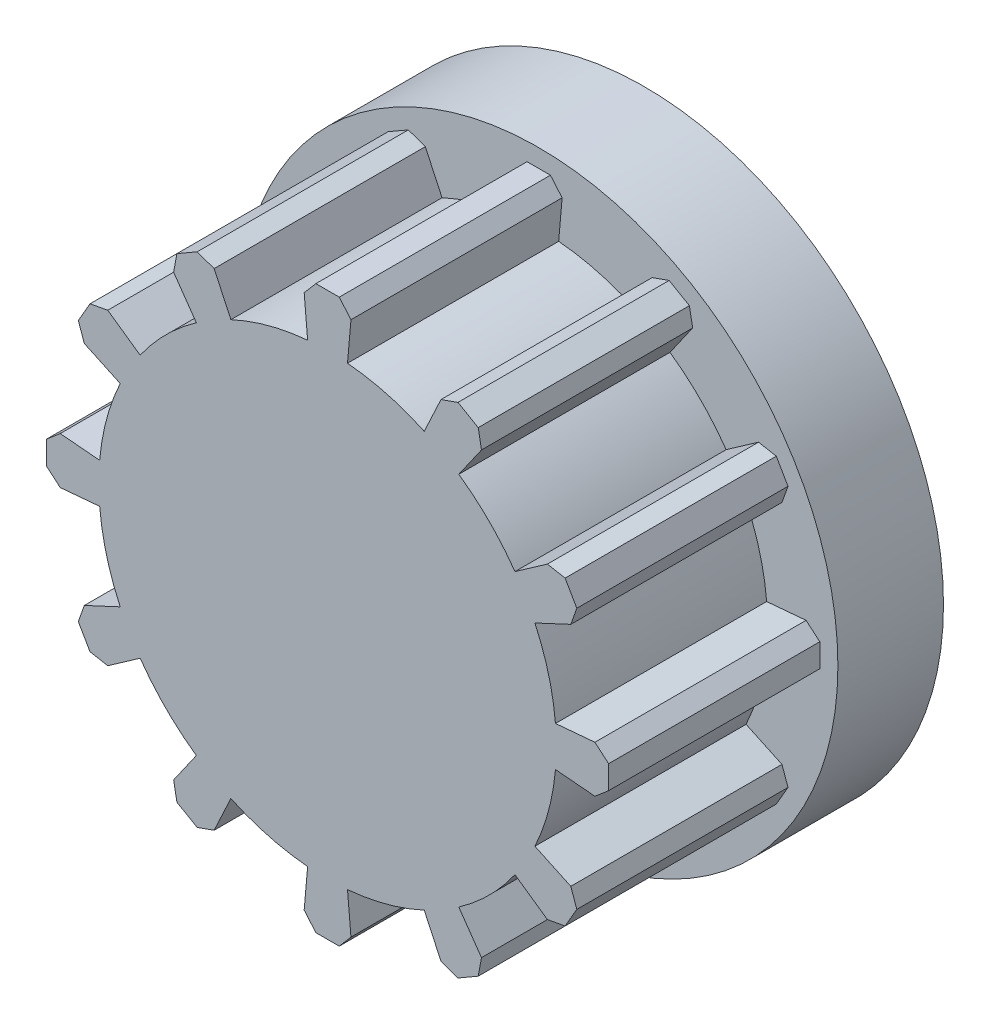
SolidWorks part; units mm, degrees
ref_plane "Front Plane" through (0, 0, 0) normal (0, 0, 1) x (1, 0, 0)
ref_plane "Top Plane" through (0, 0, 0) normal (0, 1, 0) x (1, 0, 0)
ref_plane "Right Plane" through (0, 0, 0) normal (1, 0, 0) x (0, 0, -1)
sketch "Sketch1" plane through (0, 0, 0) normal (0, 0, 1) x (1, 0, 0)
  circle A0 centre (0, 0) radius 8.5
extrude "Boss-Extrude1" add sketch "Sketch1" along normal blind 3
sketch "Sketch2" plane through (0, 0, 3) normal (0, 0, 1) x (1, 0, 0)
  line L0 (2.747, 5.891) -> (3.2225, 6.9106)
  line L1 (-0.5665, 6.4753) -> (-0.6646, 7.596) construction
  line L2 (-0.5665, 6.4753) -> (-0.6646, 7.596)
  line L3 (3.2225, 6.9106) -> (3.705, 7.0818)
  line L4 (-0.6646, 7.596) -> (-0.3323, 7.9855)
  line L5 (0.5665, 6.4753) -> (0.6646, 7.596)
  line L6 (0.6646, 7.596) -> (0.3323, 7.9855)
  line L7 (-0.3323, 7.9855) -> (0.3323, 7.9855)
  line L9 (3.7282, 5.3245) -> (4.3735, 6.246)
  line L10 (4.3735, 6.246) -> (4.2805, 6.7495)
  line L11 (3.705, 7.0818) -> (4.2805, 6.7495)
  line L13 (5.3245, 3.7282) -> (6.246, 4.3735)
  line L14 (6.246, 4.3735) -> (6.7495, 4.2805)
  line L15 (5.891, 2.747) -> (6.9106, 3.2225)
  line L16 (6.9106, 3.2225) -> (7.0818, 3.705)
  line L17 (6.7495, 4.2805) -> (7.0818, 3.705)
  line L19 (6.4753, 0.5665) -> (7.596, 0.6646)
  line L20 (7.596, 0.6646) -> (7.9855, 0.3323)
  line L21 (6.4753, -0.5665) -> (7.596, -0.6646)
  line L22 (7.596, -0.6646) -> (7.9855, -0.3323)
  line L23 (7.9855, 0.3323) -> (7.9855, -0.3323)
  line L25 (5.891, -2.747) -> (6.9106, -3.2225)
  line L26 (6.9106, -3.2225) -> (7.0818, -3.705)
  line L27 (5.3245, -3.7282) -> (6.246, -4.3735)
  line L28 (6.246, -4.3735) -> (6.7495, -4.2805)
  line L29 (7.0818, -3.705) -> (6.7495, -4.2805)
  line L30 (7.253, -4.1875) -> (7.7711, -4.4867) construction
  line L31 (3.7282, -5.3245) -> (4.3735, -6.246)
  line L32 (4.3735, -6.246) -> (4.2805, -6.7495)
  line L33 (2.747, -5.891) -> (3.2225, -6.9106)
  line L34 (3.2225, -6.9106) -> (3.705, -7.0818)
  line L35 (4.2805, -6.7495) -> (3.705, -7.0818)
  line L37 (0.5665, -6.4753) -> (0.6646, -7.596)
  line L38 (0.6646, -7.596) -> (0.3323, -7.9855)
  line L39 (-0.5665, -6.4753) -> (-0.6646, -7.596)
  line L40 (-0.6646, -7.596) -> (-0.3323, -7.9855)
  line L41 (0.3323, -7.9855) -> (-0.3323, -7.9855)
  line L43 (-2.747, -5.891) -> (-3.2225, -6.9106)
  line L44 (-3.2225, -6.9106) -> (-3.705, -7.0818)
  line L45 (-3.7282, -5.3245) -> (-4.3735, -6.246)
  line L46 (-4.3735, -6.246) -> (-4.2805, -6.7495)
  line L47 (-3.705, -7.0818) -> (-4.2805, -6.7495)
  line L49 (-5.3245, -3.7282) -> (-6.246, -4.3735)
  line L50 (-6.246, -4.3735) -> (-6.7495, -4.2805)
  line L51 (-5.891, -2.747) -> (-6.9106, -3.2225)
  line L52 (-6.9106, -3.2225) -> (-7.0818, -3.705)
  line L53 (-6.7495, -4.2805) -> (-7.0818, -3.705)
  line L55 (-6.4753, -0.5665) -> (-7.596, -0.6646)
  line L56 (-7.596, -0.6646) -> (-7.9855, -0.3323)
  line L57 (-6.4753, 0.5665) -> (-7.596, 0.6646)
  line L58 (-7.596, 0.6646) -> (-7.9855, 0.3323)
  line L59 (-7.9855, -0.3323) -> (-7.9855, 0.3323)
  line L61 (-5.891, 2.747) -> (-6.9106, 3.2225)
  line L62 (-6.9106, 3.2225) -> (-7.0818, 3.705)
  line L63 (-5.3245, 3.7282) -> (-6.246, 4.3735)
  line L64 (-6.246, 4.3735) -> (-6.7495, 4.2805)
  line L65 (-7.0818, 3.705) -> (-6.7495, 4.2805)
  line L67 (-3.7282, 5.3245) -> (-4.3735, 6.246)
  line L68 (-4.3735, 6.246) -> (-4.2805, 6.7495)
  line L69 (-2.747, 5.891) -> (-3.2225, 6.9106)
  line L70 (-3.2225, 6.9106) -> (-3.705, 7.0818)
  line L71 (-4.2805, 6.7495) -> (-3.705, 7.0818)
  circle A1 centre (0, 0) radius 6.5
  point P102 (0, 0)
  dimension "D1" = 12
  dimension "D2" = 13
  dimension "D4" = 7.625
sketch "Sketch4" plane through (0, 0, 0) normal (0, 0, -1) x (-1, 0, 0)
  line L0 (-3.25, 0.9682) -> (3.25, 0.9682)
  line L1 (-3.25, -0.9682) -> (3.25, -0.9682)
  line L2 (-5, 0) -> (5, 0) construction
  arc A0 (-3.25, 0.9682) -> (-3.25, -0.9682) centre (-5, 0) ccw
  arc A1 (3.25, -0.9682) -> (3.25, 0.9682) centre (5, 0) ccw
  point P2 (0.1492, 0.8866)
  point P3 (0.1492, 0.8866)
  point P8 (0, 0)
  dimension "D1" = 10
extrude "Cut-Extrude2" cut sketch "Sketch4" against normal blind 2
extrude "Boss-Extrude4" add sketch "Sketch2" along normal blind 6 contours A1 L63 L64 L65 L62 L61 | A1 L69 L70 L71 L68 L67 | A1 L9 L10 L11 L3 L0 | A1 L15 L16 L17 L14 L13 | A1 L21 L22 L23 L20 L19 | A1 L27 L28 L29 L26 L25 | A1 L33 L34 L35 L32 L31 | A1 L39 L40 L41 L38 L37 | A1 L45 L46 L47 L44 L43 | A1 L51 L52 L53 L50 L49 | A1 L57 L58 L59 L56 L55 | A1 L5 L6 L7 L4 L2 | A1 L27
